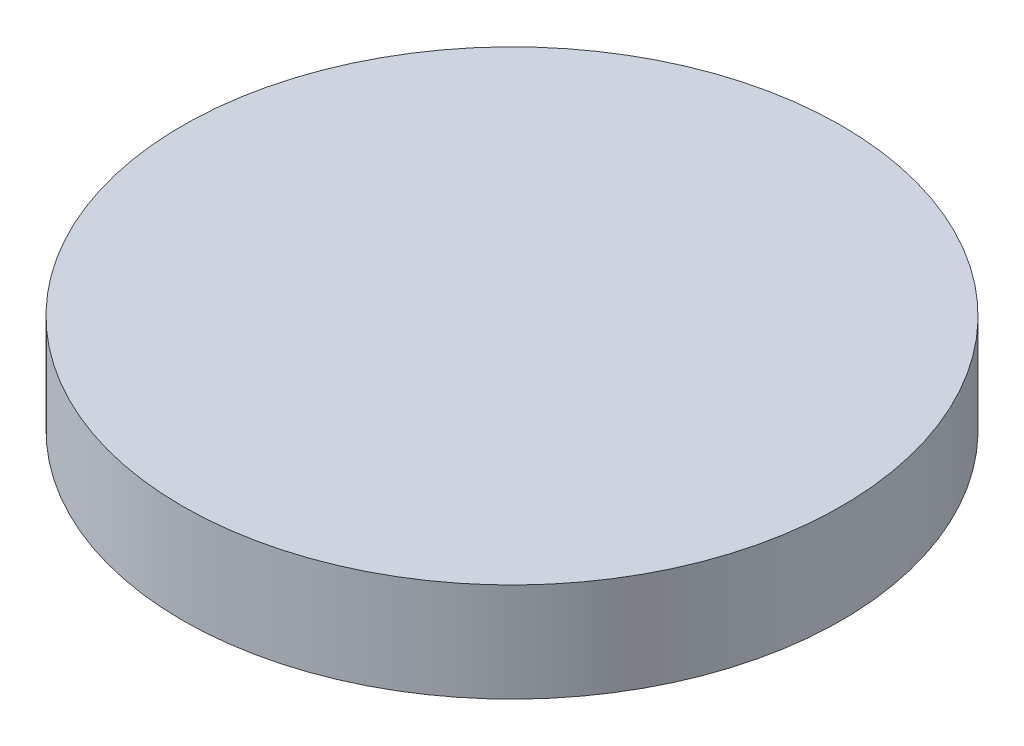
SolidWorks part; units mm, degrees
ref_plane "Front Plane" through (0, 0, 0) normal (0, 0, 1) x (1, 0, 0)
ref_plane "Top Plane" through (0, 0, 0) normal (0, 1, 0) x (1, 0, 0)
ref_plane "Right Plane" through (0, 0, 0) normal (1, 0, 0) x (0, 0, -1)
sketch "Sketch1" plane through (0, 0, 0) normal (0, 1, 0) x (1, 0, 0)
  circle A0 centre (0, 0) radius 25.4
extrude "Boss-Extrude2" add sketch "Sketch1" along normal blind 7.62 contours A0
sketch "Sketch4" plane through (0, 0, 0) normal (0, 1, 0) x (1, 0, 0)
  circle A0 centre (0, 0) radius 17.78 construction
  circle A1 centre (0, 17.78) radius 4.826
  point P5 (0, 0)
extrude "Cut-Extrude2" cut sketch "Sketch4" along normal blind 3.048
pattern_circular "CirPattern1" count 6 over 360 about axis through (0, 0, 0) along (0, 1, 0) of "Cut-Extrude2"
sketch "Sketch5" plane through (0, 0, 0) normal (0, 1, 0) x (1, 0, 0)
  circle A0 centre (0, 0) radius 4.826
sketch "Sketch6" plane through (0, 7.62, 0) normal (0, 1, 0) x (1, 0, 0)
  circle A0 centre (0, 0) radius 12.7
extrude "Boss-Extrude4" [suppressed] add sketch "Sketch6" along normal blind 41.91 draft 7
extrude "Cut-Extrude6" cut sketch "Sketch5" along normal blind 3.048
sketch "Sketch7" plane through (0, 0, 0) normal (0, -1, 0) x (1, 0, 0)
  line L0 (0, 17.78) -> (0, -0.3504) construction
  line L1 (0, -0.3504) -> (0, 0) construction
  line L2 (0, 0) -> (15.7022, 8.7148) construction
  line L3 (15.7022, 8.7148) -> (0, 17.78) construction
  line L4 (0, 17.78) -> (0, 0) construction
  line L5 (0, 0) -> (7.8511, 13.2474) construction
  circle A0 centre (0, 0) radius 8.89 construction
  circle A1 centre (4.5325, 7.6478) radius 1.5875
  circle A2 centre (4.3569, -7.7491) radius 1.5875
  circle A3 centre (-8.8894, 0.1014) radius 1.5875
  point P16 (0, 0)
  dimension "D1" = 3
extrude "Cut-Extrude7" cut sketch "Sketch7" against normal blind 1.5875
